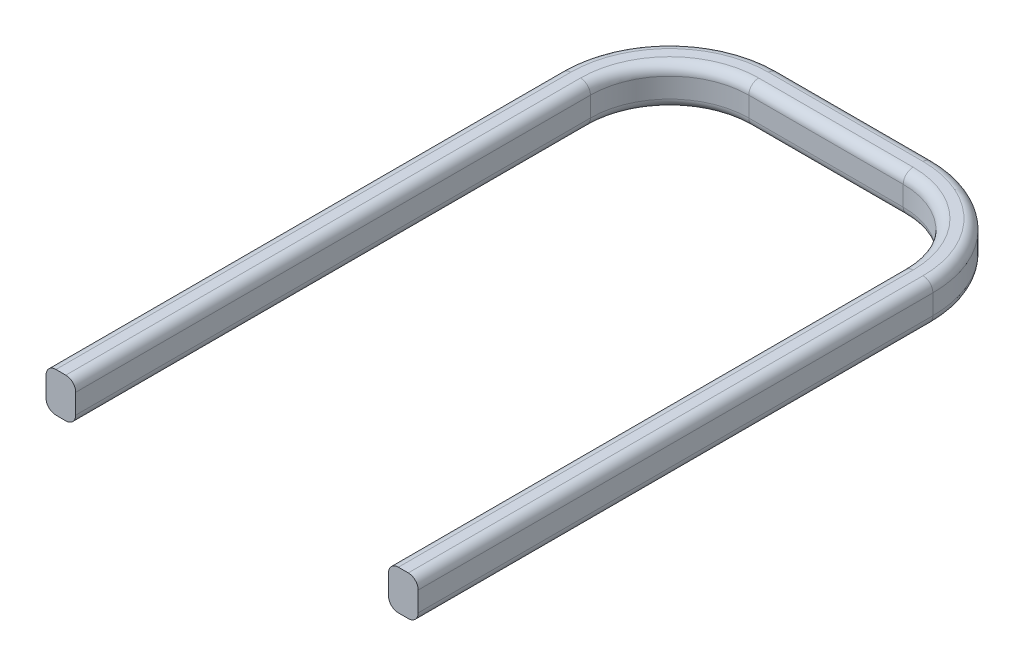
SolidWorks part; units mm, degrees
ref_plane "Front Plane" through (0, 0, 0) normal (0, 0, 1) x (1, 0, 0)
ref_plane "Top Plane" through (0, 0, 0) normal (0, 1, 0) x (1, 0, 0)
ref_plane "Right Plane" through (0, 0, 0) normal (1, 0, 0) x (0, 0, -1)
sketch "Sketch1" plane through (0, 0, 0) normal (0, 1, 0) x (1, 0, 0)
  line L0 (-3.95, 0) -> (-3.95, 13)
  line L1 (-1.95, 15) -> (1.95, 15)
  line L2 (3.95, 13) -> (3.95, 0)
  line L3 (0, 0) -> (0, 16.9771) construction
  line L4 (-4.7, 0) -> (-4.7, 13)
  line L5 (-1.95, 15.75) -> (1.95, 15.75)
  line L6 (4.7, 13) -> (4.7, 0)
  line L7 (-4.7, 0) -> (-3.95, 0)
  line L8 (3.95, 0) -> (4.7, 0)
  arc A0 (1.95, 15) -> (3.95, 13) centre (1.95, 13) cw
  arc A1 (-3.95, 13) -> (-1.95, 15) centre (-1.95, 13) cw
  arc A2 (-4.7, 13) -> (-1.95, 15.75) centre (-1.95, 13) cw
  arc A3 (1.95, 15.75) -> (4.7, 13) centre (1.95, 13) cw
  point P12 (-3.95, 15)
  dimension "D3" = 2
  dimension "D1" = 15
  dimension "D2" = 3.95
  dimension "D4" = 0.75
extrude "Boss-Extrude1" add sketch "Sketch1" along normal blind 1
fillet "Fillet1" radius 0.25 20 edges at (-3.95, 0, -6.5) (-3.3642, 0, -14.4142) (0, 0, -15) (3.3642, 0, -14.4142) (3.95, 0, -6.5) (4.7, 0, -6.5) (3.8945, 0, -14.9445) (0, 0, -15.75) (-3.8945, 0, -14.9445) (-4.7, 0, -6.5) (-4.7, 1, -6.5) (-3.8945, 1, -14.9445) (0, 1, -15.75) (3.8945, 1, -14.9445) (4.7, 1, -6.5) (3.95, 1, -6.5) (3.3642, 1, -14.4142) (0, 1, -15) (-3.3642, 1, -14.4142) (-3.95, 1, -6.5)
